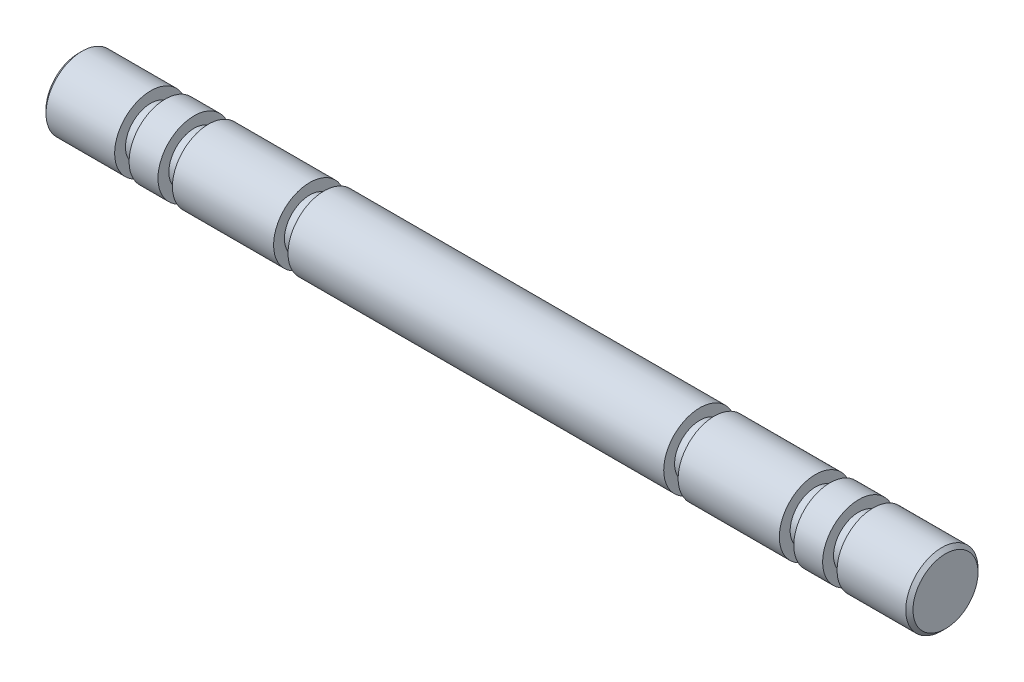
SolidWorks part; units mm, degrees
ref_plane "前视基准面" through (0, 0, 0) normal (0, 0, 1) x (1, 0, 0)
ref_plane "上视基准面" through (0, 0, 0) normal (0, 1, 0) x (1, 0, 0)
ref_plane "右视基准面" through (0, 0, 0) normal (1, 0, 0) x (0, 0, -1)
sketch "草图1" plane through (0, 0, 0) normal (1, 0, 0) x (0, 0, -1)
  circle A0 centre (0, 0) radius 5
  dimension "D1" = 10
extrude "凸台-拉伸1" add sketch "草图1" along normal blind 52
sketch "草图2" plane through (52, 0, 0) normal (1, 0, 0) x (0, 0, -1)
  circle A0 centre (0, 0) radius 3.5
  dimension "D1" = 7
extrude "凸台-拉伸2" add sketch "草图2" along normal blind 2
sketch "草图3" plane through (54, 0, 0) normal (1, 0, 0) x (0, 0, -1)
  circle A0 centre (0, 0) radius 5
  dimension "D1" = 10
extrude "凸台-拉伸3" add sketch "草图3" along normal blind 14
sketch "草图4" plane through (68, 0, 0) normal (1, 0, 0) x (0, 0, -1)
  circle A0 centre (0, 0) radius 3.5
  dimension "D1" = 7
extrude "凸台-拉伸4" add sketch "草图4" along normal blind 2
sketch "草图5" plane through (70, 0, 0) normal (1, 0, 0) x (0, 0, -1)
  circle A0 centre (0, 0) radius 5
  dimension "D1" = 10
extrude "凸台-拉伸5" add sketch "草图5" along normal blind 4
sketch "草图6" plane through (74, 0, 0) normal (1, 0, 0) x (0, 0, -1)
  circle A0 centre (0, 0) radius 3.5
  dimension "D1" = 7
extrude "凸台-拉伸6" add sketch "草图6" along normal blind 2
sketch "草图7" plane through (76, 0, 0) normal (1, 0, 0) x (0, 0, -1)
  circle A0 centre (0, 0) radius 5
  dimension "D1" = 10
extrude "凸台-拉伸7" add sketch "草图7" along normal blind 10
sketch "草图8" plane through (0, 0, 0) normal (-1, 0, 0) x (0, 0, 1)
  circle A0 centre (0, 0) radius 3.5
  dimension "D1" = 7
extrude "凸台-拉伸8" add sketch "草图8" along normal blind 2
sketch "草图9" plane through (-2, 0, 0) normal (-1, 0, 0) x (0, 0, 1)
  circle A0 centre (0, 0) radius 5
  dimension "D1" = 10
extrude "凸台-拉伸9" add sketch "草图9" along normal blind 14
sketch "草图10" plane through (-16, 0, 0) normal (-1, 0, 0) x (0, 0, 1)
  circle A0 centre (0, 0) radius 3.5
  dimension "D1" = 7
extrude "凸台-拉伸10" add sketch "草图10" along normal blind 2
sketch "草图11" plane through (-18, 0, 0) normal (-1, 0, 0) x (0, 0, 1)
  circle A0 centre (0, 0) radius 5
  dimension "D1" = 10
extrude "凸台-拉伸11" add sketch "草图11" along normal blind 4
sketch "草图12" plane through (-22, 0, 0) normal (-1, 0, 0) x (0, 0, 1)
  circle A0 centre (0, 0) radius 3.5
  dimension "D1" = 7
extrude "凸台-拉伸12" add sketch "草图12" along normal blind 2
sketch "草图13" plane through (-24, 0, 0) normal (-1, 0, 0) x (0, 0, 1)
  circle A0 centre (0, 0) radius 5
  dimension "D1" = 10
extrude "凸台-拉伸13" add sketch "草图13" along normal blind 10
chamfer "倒角1" distance 0.5 angle 45 2 edges at (-34, 0, 5) (86, 0, -5)
